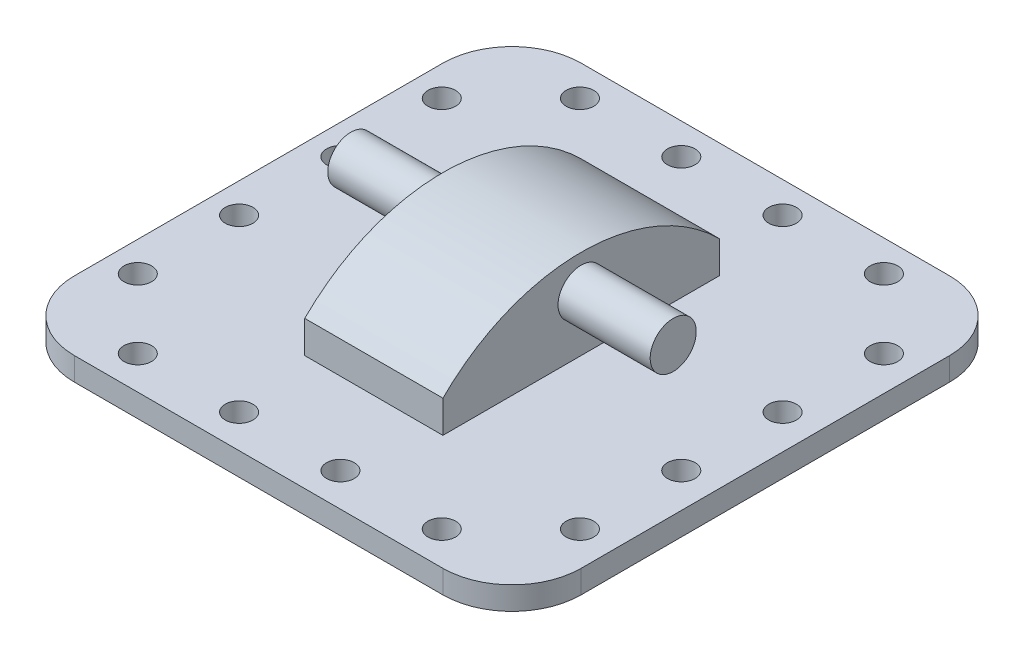
SolidWorks part; units mm, degrees
ref_plane "Front Plane" through (0, 0, 0) normal (0, 0, 1) x (1, 0, 0)
ref_plane "Top Plane" through (0, 0, 0) normal (0, 1, 0) x (1, 0, 0)
ref_plane "Right Plane" through (0, 0, 0) normal (1, 0, 0) x (0, 0, -1)
sketch "Sketch1" plane through (0, 0, 0) normal (0, 1, 0) x (1, 0, 0)
  line L1 (-55, -55) -> (55, -55)
  line L2 (-55, -55) -> (-55, 55)
  line L3 (-55, 55) -> (55, 55)
  line L4 (55, -55) -> (55, 55)
  line L5 (-55, -55) -> (55, 55) construction
  line L6 (-55, 55) -> (55, -55) construction
  point P0 (0, 0)
  point P6 (0, 0)
  point P7 (-53.1356, 47.161)
  point P8 (-53.6441, 47.4153)
  point P9 (0, 0)
  point P10 (60, -52.7542)
  dimension "D1" = 110
  dimension "D2" = 110
extrude "Boss-Extrude1" add sketch "Sketch1" along normal blind 5
fillet "Fillet2" radius 15 1 edges at (55, 2.5, -55)
fillet "Fillet3" radius 15 1 edges at (-55, 2.5, -55)
fillet "Fillet4" radius 15 1 edges at (-55, 2.5, 55)
fillet "Fillet5" radius 15 1 edges at (55, 2.5, 55)
sketch "Sketch2" plane through (0, 5, 0) normal (0, 1, 0) x (1, 0, 0)
  line L1 (-15, -30) -> (15, -30)
  line L2 (-15, -30) -> (-15, 30)
  line L3 (-15, 30) -> (15, 30)
  line L4 (15, -30) -> (15, 30)
  line L5 (-15, -30) -> (15, 30) construction
  line L6 (-15, 30) -> (15, -30) construction
  point P0 (0, 0)
extrude "Boss-Extrude2" add sketch "Sketch2" along normal blind 24
sketch "Sketch4" plane through (15, 0, 0) normal (1, 0, 0) x (0, 0, -1)
  line L0 (-30, 17) -> (30, 17) construction
  line L1 (-30, 29) -> (-30, 5) construction
  line L2 (30, 29) -> (30, 5) construction
  line L3 (0, 17) -> (0, 29) construction
  line L4 (-30, 29) -> (30, 29) construction
  line L5 (0, 29) -> (0, 5) construction
  line L6 (-40, 5) -> (40, 5) construction
  circle A2 centre (0, 17) radius 5
extrude "Boss-Extrude3" add sketch "Sketch4" along normal blind 20 and the other way blind 50
fillet "Fillet6" radius 10 1 edges at (0, 29, 30)
fillet "Fillet7" radius 10 1 edges at (0, 29, -30)
sketch "Sketch5" plane through (0, 0, 0) normal (0, -1, 0) x (1, 0, 0)
  line L0 (54.498, -40.251) -> (54.498, 39.749)
  line L1 (39.498, 54.749) -> (-40.502, 54.749)
  line L2 (-55.502, 39.749) -> (-55.502, -40.251)
  line L3 (-40.502, -55.251) -> (39.498, -55.251)
  circle A0 centre (47.498, -11.251) radius 3
  circle A1 centre (47.498, 32.749) radius 3
  circle A2 centre (-48.502, 10.749) radius 3
  circle A3 centre (-48.502, -11.251) radius 3
  circle A4 centre (-48.502, -33.251) radius 3
  circle A5 centre (-33.502, -48.251) radius 3
  circle A6 centre (-11.502, -48.251) radius 3
  circle A7 centre (10.498, -48.251) radius 3
  circle A8 centre (32.498, -48.251) radius 3
  circle A9 centre (47.498, -33.251) radius 3
  circle A10 centre (47.498, 10.749) radius 3
  circle A11 centre (32.498, 47.749) radius 3
  circle A12 centre (10.498, 47.749) radius 3
  circle A13 centre (-11.502, 47.749) radius 3
  circle A14 centre (-33.502, 47.749) radius 3
  circle A15 centre (-48.502, 32.749) radius 3
  arc A16 (54.498, 39.749) -> (39.498, 54.749) centre (39.498, 39.749) ccw
  arc A17 (-40.502, 54.749) -> (-55.502, 39.749) centre (-40.502, 39.749) ccw
  arc A18 (-55.502, -40.251) -> (-40.502, -55.251) centre (-40.502, -40.251) ccw
  arc A19 (39.498, -55.251) -> (54.498, -40.251) centre (39.498, -40.251) ccw
extrude "Cut-Extrude2" cut sketch "Sketch5" against normal blind 10 contours A5 | A4 | A3 | A2 | A1 | A0 | A7 | A6 | A15 | A14 | A13 | A12 | A11 | A10 | A9 | A8
sketch "Sketch6" plane through (0, 5, 0) normal (0, 1, 0) x (1, 0, 0)
  line L1 (-15, 30) -> (15, 30)
  line L2 (-15, 30) -> (-15, -30)
  line L3 (-15, -30) -> (15, -30)
  line L4 (15, 30) -> (15, -30)
sketch "Sketch8" plane through (-15, 0, 0) normal (-1, 0, 0) x (0, 0, 1)
  line L0 (-30, 19) -> (-30, 5) construction
  line L1 (30, 19) -> (30, 5) construction
  line L2 (-20, 29) -> (20, 29) construction
  line L3 (-30, 19) -> (-30, 12)
  line L4 (30, 19) -> (30, 12)
  line L5 (-20, 29) -> (20, 29)
  arc A0 (-30, 12) -> (30, 12) centre (0, -18) cw
  arc A1 (-20, 29) -> (-30, 19) centre (-20, 19) ccw construction
  arc A2 (30, 19) -> (20, 29) centre (20, 19) ccw construction
  arc A3 (-20, 29) -> (-30, 19) centre (-20, 19) ccw
  arc A4 (30, 19) -> (20, 29) centre (20, 19) ccw
extrude "Cut-Extrude3" cut sketch "Sketch8" against normal blind 60
